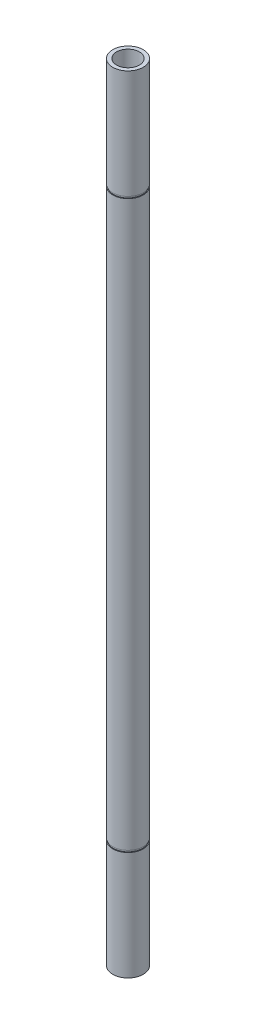
SolidWorks part; units mm, degrees
material "1060 Alloy"
ref_plane "Front Plane" through (0, 0, 0) normal (0, 0, 1) x (1, 0, 0)
ref_plane "Top Plane" through (0, 0, 0) normal (0, 1, 0) x (1, 0, 0)
ref_plane "Right Plane" through (0, 0, 0) normal (1, 0, 0) x (0, 0, -1)
sketch "Sketch1" plane through (0, 0, 0) normal (0, 0, 1) x (1, 0, 0)
  line L0 (0, 64.3023) -> (0, -80.2699) construction
  line L1 (-3, 103) -> (-4, 103)
  line L2 (-4, 103) -> (-4, 74.5)
  line L3 (-4, 74.5) -> (-3.8, 74.5)
  line L4 (-3.8, 74.5) -> (-3.8, 74)
  line L5 (-3.8, 74) -> (-4, 74)
  line L6 (-30.6471, 0) -> (35.9901, 0) construction
  line L7 (-4, 74) -> (-4, -74)
  line L8 (-3.8, -74) -> (-4, -74)
  line L9 (-3.8, -74.5) -> (-3.8, -74)
  line L10 (-4, -74.5) -> (-3.8, -74.5)
  line L11 (-4, -103) -> (-4, -74.5)
  line L12 (-3, -103) -> (-4, -103)
  line L13 (-3, 103) -> (-3, -103)
  point P11 (-4, 88.75)
  point P14 (-4, 0)
  dimension "D1" = 206
  dimension "D2" = 8
  dimension "D3" = 0.5
  dimension "D4" = 0.2
  dimension "D5" = 28.5
  dimension "D6" = 1
revolve "Revolve2" add sketch "Sketch1" angle 360 about L0
